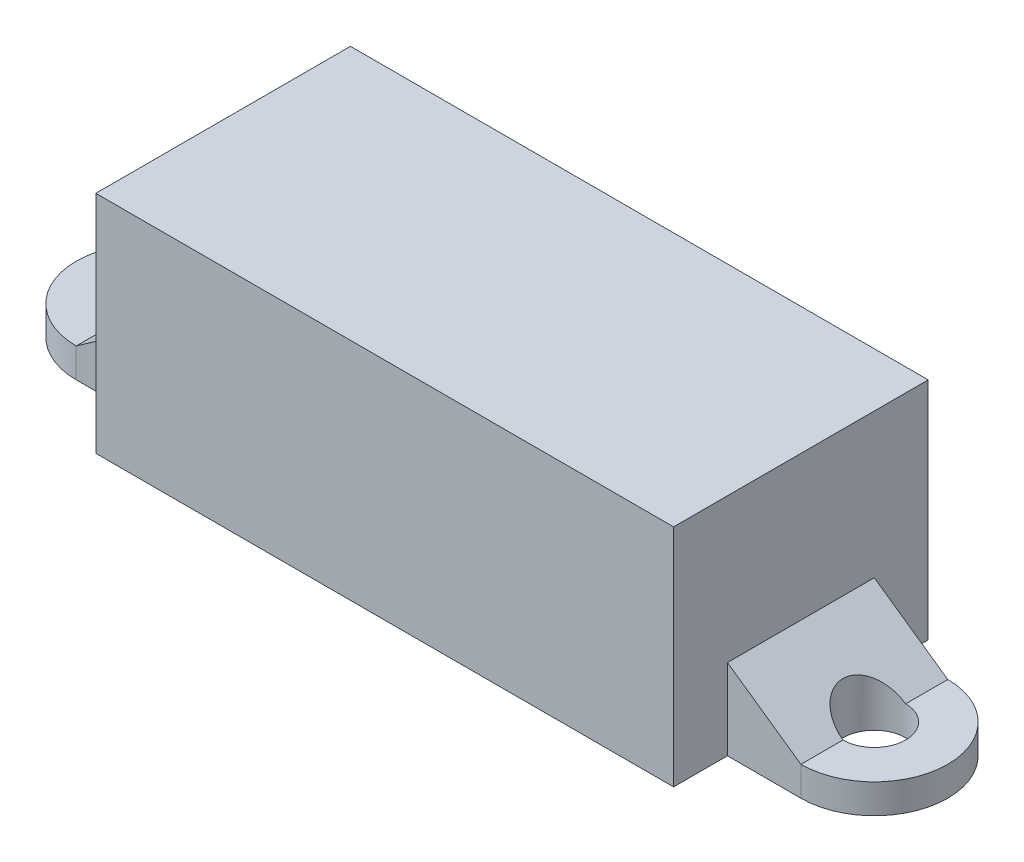
SolidWorks part; units mm, degrees
ref_plane "Alzado" through (0, 0, 0) normal (0, 0, 1) x (1, 0, 0)
ref_plane "Planta" through (0, 0, 0) normal (0, 1, 0) x (1, 0, 0)
ref_plane "Vista lateral" through (0, 0, 0) normal (1, 0, 0) x (0, 0, -1)
sketch "Croquis1" plane through (0, 0, 0) normal (0, 1, 0) x (1, 0, 0)
  line L0 (0, 0) -> (0, -12.3092) construction
  line L1 (-14.75, -6.5) -> (14.75, -6.5)
  line L2 (-14.75, -6.5) -> (-14.75, -3.75)
  line L3 (-14.75, 6.5) -> (14.75, 6.5)
  line L4 (14.75, -6.5) -> (14.75, -3.75)
  line L5 (-14.75, -6.5) -> (14.75, 6.5) construction
  line L6 (-14.75, 6.5) -> (14.75, -6.5) construction
  line L7 (-18.5, 3.75) -> (-14.75, 3.75)
  line L8 (0, 0) -> (0, 15.1498) construction
  line L9 (-18.5, -3.75) -> (-14.75, -3.75)
  line L10 (18.5, 3.75) -> (14.75, 3.75)
  line L11 (18.5, -3.75) -> (14.75, -3.75)
  line L12 (-14.75, 3.75) -> (-14.75, 6.5)
  line L13 (14.75, 3.75) -> (14.75, 6.5)
  arc A1 (-18.5, 3.75) -> (-18.5, -3.75) centre (-18.5, 0) ccw
  circle A2 centre (-18.5, 0) radius 1.6
  circle A3 centre (18.5, 0) radius 1.6
  arc A4 (18.5, 3.75) -> (18.5, -3.75) centre (18.5, 0) cw
  point P0 (0, 0)
  dimension "D3" = 3.2
  dimension "D4" = 7.5
  dimension "D1" = 29.5
  dimension "D2" = 13
  dimension "D5" = 18.5
extrude "Saliente-Extruir2" add sketch "Croquis1" along normal blind 11.5
sketch "Croquis2" plane through (0, 0, 0) normal (0, 0, 1) x (1, 0, 0)
  line L0 (22.25, 0) -> (22.25, 1.5)
  line L1 (22.25, 0) -> (22.25, 11.5) construction
  line L2 (22.25, 1.5) -> (18.5, 1.5)
  line L3 (18.5, 11.5) -> (18.5, 0) construction
  line L4 (18.5, 1.5) -> (14.75, 4.1258)
  line L5 (14.75, 11.5) -> (14.75, 0) construction
  line L6 (14.75, 4.1258) -> (14.75, 11.5)
  line L7 (14.75, 11.5) -> (18.5, 11.5) construction
  line L8 (14.75, 11.5) -> (22.25, 11.5)
  line L9 (22.25, 11.5) -> (22.25, 1.5)
  line L10 (0, 0) -> (0, 13.5478) construction
  line L11 (-14.75, 0) -> (14.75, 0) construction
  line L12 (-22.25, 11.5) -> (-22.25, 1.5)
  line L13 (-14.75, 11.5) -> (-22.25, 11.5)
  line L14 (-14.75, 4.1258) -> (-14.75, 11.5)
  line L15 (-18.5, 1.5) -> (-14.75, 4.1258)
  line L16 (-22.25, 1.5) -> (-18.5, 1.5)
  dimension "D1" = 1.5
  dimension "D2" = 145
extrude "Cortar-Extruir1" cut sketch "Croquis2" against normal through all both and the other way through all contours L9 L8 L6 L4 L2 | L12 L16 L15 L14 L13
